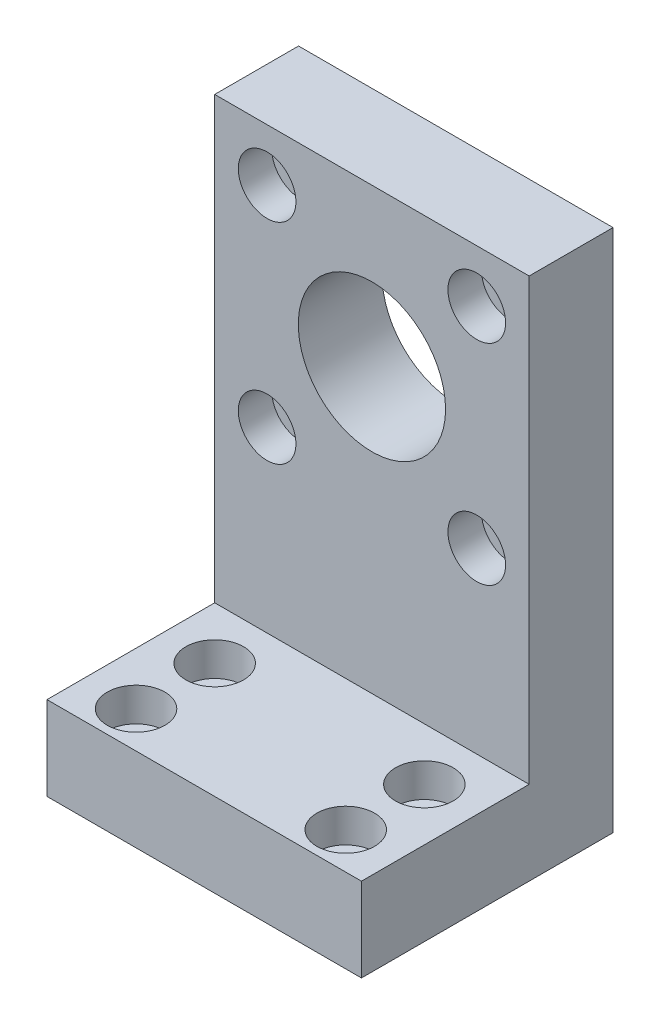
SolidWorks part; units mm, degrees
ref_plane "Front Plane" through (0, 0, 0) normal (0, 0, 1) x (1, 0, 0)
ref_plane "Top Plane" through (0, 0, 0) normal (0, 1, 0) x (1, 0, 0)
ref_plane "Right Plane" through (0, 0, 0) normal (1, 0, 0) x (0, 0, -1)
sketch "Sketch1" plane through (0, 0, 0) normal (0, 0, 1) x (1, 0, 0)
  line L1 (-30, 50) -> (30, 50)
  line L2 (-30, 50) -> (-30, -50)
  line L3 (-30, -50) -> (30, -50)
  line L4 (30, 50) -> (30, -50)
  line L5 (-30, 50) -> (30, -50) construction
  line L6 (-30, -50) -> (30, 50) construction
  point P0 (0, 0)
  dimension "D1" = 100
  dimension "D2" = 60
extrude "Boss-Extrude1" add sketch "Sketch1" along normal mid plane 16 contours L2 L3 L4 L1
hole_wizard "CBORE for M6 Hex Socket Head Cap Screw1" positions "Sketch2" profile "Sketch3" counterbore size "M6" standard "ISO" end condition through all
sketch "Sketch2" plane through (0, 0, 8) normal (0, 0, 1) x (1, 0, 0)
  line L0 (-30, -50) -> (30, -50) construction
  point P0 (-20, 40)
  point P2 (20, 40)
  point P4 (20, 0)
  point P6 (-20, 0)
  dimension "D1" = 40
  dimension "D2" = 20
  dimension "D3" = 40
  dimension "D4" = 50
sketch "Sketch3" plane through (-20, 40, 8) normal (1, 0, 0) x (0, -1, 0)
  line L0 (0, 0) -> (0, 16)
  line L1 (0, 16) -> (3.3, 16)
  line L3 (3.3, 16) -> (3.3, 6.4)
  line L4 (3.3, 6.4) -> (5.5, 6.4)
  line L5 (5.5, 6.4) -> (5.5, 0)
  line L7 (5.5, 0) -> (0, 0)
  line L11 (0, -6.35) -> (0, 107.95) construction
  dimension "Thru Hole Dia." = 6.6
  dimension "Thru Hole Depth" = 16
  dimension "C'Bore Dia." = 11
  dimension "C'Bore Depth" = 6.4
sketch "Sketch6" plane through (0, 0, 8) normal (0, 0, 1) x (1, 0, 0)
  circle A0 centre (0, 20) radius 14.05
  circle A1 centre (-20, 0) radius 3.3 construction
  circle A2 centre (-20, 0) radius 5.5 construction
  dimension "D2" = 20
  dimension "D3" = 28.1
  dimension "D1" = 20
extrude "Cut-Extrude1" cut sketch "Sketch6" against normal through all contours A0
sketch "Sketch7" plane through (0, 0, 8) normal (0, 0, 1) x (1, 0, 0)
  line L0 (30, 50) -> (30, -50) construction
  line L1 (-30, -50) -> (30, -50)
  line L2 (-30, -50) -> (-30, -34)
  line L3 (-30, -34) -> (30, -34)
  line L4 (30, -50) -> (30, -34)
  dimension "D1" = 16
extrude "Boss-Extrude2" add sketch "Sketch7" along normal blind 32
hole_wizard "CBORE for M6 Hex Socket Head Cap Screw2" positions "Sketch8" profile "Sketch9" counterbore size "M6" standard "ISO" end condition through all
sketch "Sketch8" plane through (0, -34, 0) normal (0, 1, 0) x (1, 0, 0)
  line L1 (30, -8) -> (-30, -8) construction
  point P0 (-20, -18)
  point P2 (20, -18)
  point P4 (20, -33)
  point P6 (-20, -33)
  dimension "D1" = 15
  dimension "D2" = 40
  dimension "D3" = 20
  dimension "D4" = 10
sketch "Sketch9" plane through (-20, -34, 18) normal (1, 0, 0) x (0, 0, 1)
  line L0 (0, 0) -> (0, 16)
  line L1 (0, 16) -> (3.3, 16)
  line L3 (3.3, 16) -> (3.3, 6.4)
  line L4 (3.3, 6.4) -> (5.5, 6.4)
  line L5 (5.5, 6.4) -> (5.5, 0)
  line L7 (5.5, 0) -> (0, 0)
  line L11 (0, -6.35) -> (0, 107.95) construction
  dimension "Thru Hole Dia." = 6.6
  dimension "Thru Hole Depth" = 16
  dimension "C'Bore Dia." = 11
  dimension "C'Bore Depth" = 6.4
